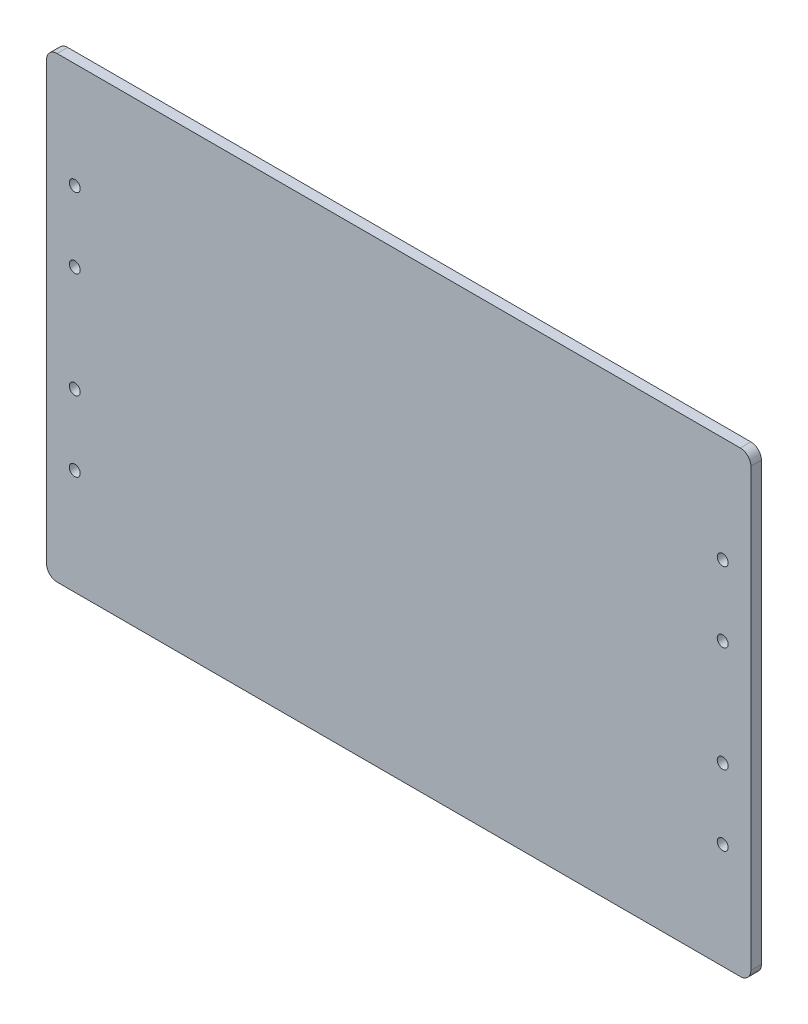
SolidWorks part; units mm, degrees
ref_plane "前视基准面" through (0, 0, 0) normal (0, 0, 1) x (1, 0, 0)
ref_plane "上视基准面" through (0, 0, 0) normal (0, 1, 0) x (1, 0, 0)
ref_plane "右视基准面" through (0, 0, 0) normal (1, 0, 0) x (0, 0, -1)
sketch "草图1" plane through (0, 0, 0) normal (0, 0, 1) x (1, 0, 0)
  line L1 (-100, 65) -> (100, 65)
  line L2 (-100, 65) -> (-100, -65)
  line L3 (-100, -65) -> (100, -65)
  line L4 (100, 65) -> (100, -65)
  line L5 (-100, 65) -> (100, -65) construction
  line L6 (-100, -65) -> (100, 65) construction
  point P0 (0, 0)
  dimension "D1" = 130
  dimension "D2" = 200
extrude "凸台-拉伸1" add sketch "草图1" along normal blind 3
sketch "草图2" plane through (0, 0, 3) normal (0, 0, 1) x (1, 0, 0)
  line L0 (0, 0) -> (-97.3003, 0) construction
  line L2 (-92, -35) -> (-92, 35) construction
  circle A0 centre (-92, 35) radius 1.55
  circle A3 centre (-92, 15) radius 1.55
  circle A6 centre (-92, -15) radius 1.55
  circle A7 centre (-92, -35) radius 1.55
  point P6 (-92, 0)
  point P8 (-130, 0)
  dimension "D3" = 3.1
  dimension "D4" = 20
  dimension "D5" = 3.1
  dimension "D1" = 70
  dimension "D2" = 92
extrude "切除-拉伸1" cut sketch "草图2" against normal blind 3
mirror "镜向1" about plane through (0, 0, 0) normal (1, 0, 0) of "切除-拉伸1"
fillet "圆角2" radius 3 4 edges at (-100, -65, 1.5) (100, -65, 1.5) (100, 65, 1.5) (-100, 65, 1.5)
